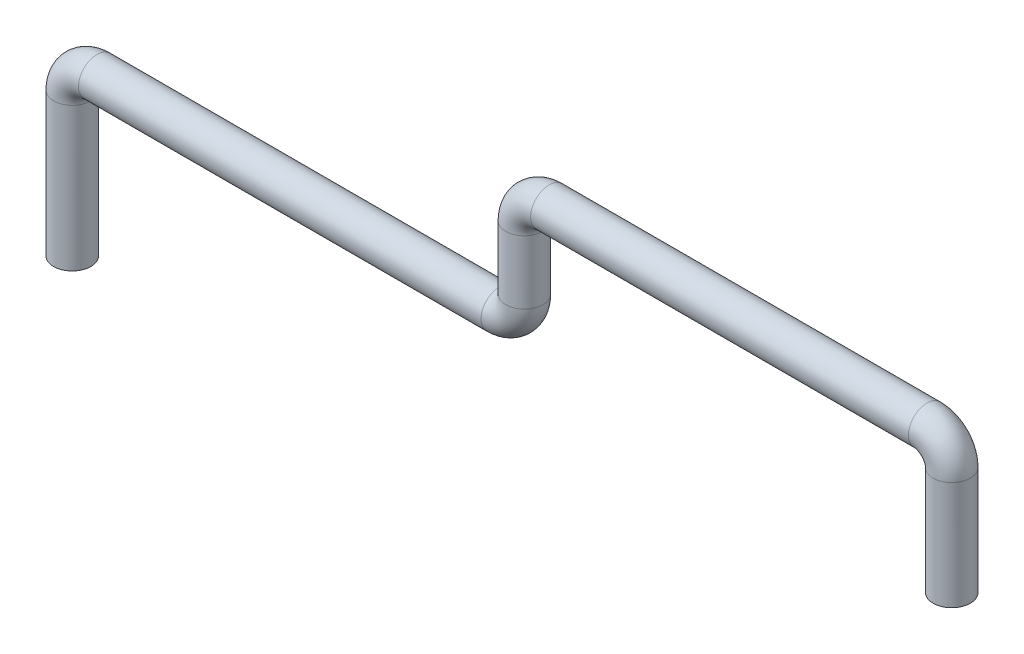
SolidWorks part; units mm, degrees
ref_plane "Front Plane" through (0, 0, 0) normal (0, 0, 1) x (1, 0, 0)
ref_plane "Top Plane" through (0, 0, 0) normal (0, 1, 0) x (1, 0, 0)
ref_plane "Right Plane" through (0, 0, 0) normal (1, 0, 0) x (0, 0, -1)
sketch "Sketch1" plane through (0, 0, 0) normal (0, 0, 1) x (1, 0, 0)
  line L0 (0, 4.6333) -> (0, 0)
  line L1 (27.6, 9.0837) -> (15.4, 9.0837)
  line L2 (28.4, 8.2837) -> (28.4, 4.7837)
  line L3 (14.6, 8.2837) -> (14.6, 6.2333)
  line L4 (13.8, 5.4333) -> (0.8, 5.4333)
  arc A0 (0.8, 5.4333) -> (0, 4.6333) centre (0.8, 4.6333) ccw
  arc A1 (27.6, 9.0837) -> (28.4, 8.2837) centre (27.6, 8.2837) cw
  arc A2 (14.6, 6.2333) -> (13.8, 5.4333) centre (13.8, 6.2333) cw
  arc A3 (15.4, 9.0837) -> (14.6, 8.2837) centre (15.4, 8.2837) ccw
  dimension "D4" = 13
  dimension "D5" = 0.8
  dimension "D6" = 0.8
  dimension "D2" = 0.8
  dimension "D1" = 12.2
  dimension "D3" = 3.5
sketch "Sketch2" plane through (0, 0, 0) normal (0, 1, 0) x (1, 0, 0)
  circle A0 centre (0, 0) radius 0.6
  dimension "D1" = 1.2
sweep "Sweep3" add profiles "Sketch2" path "Sketch1"
